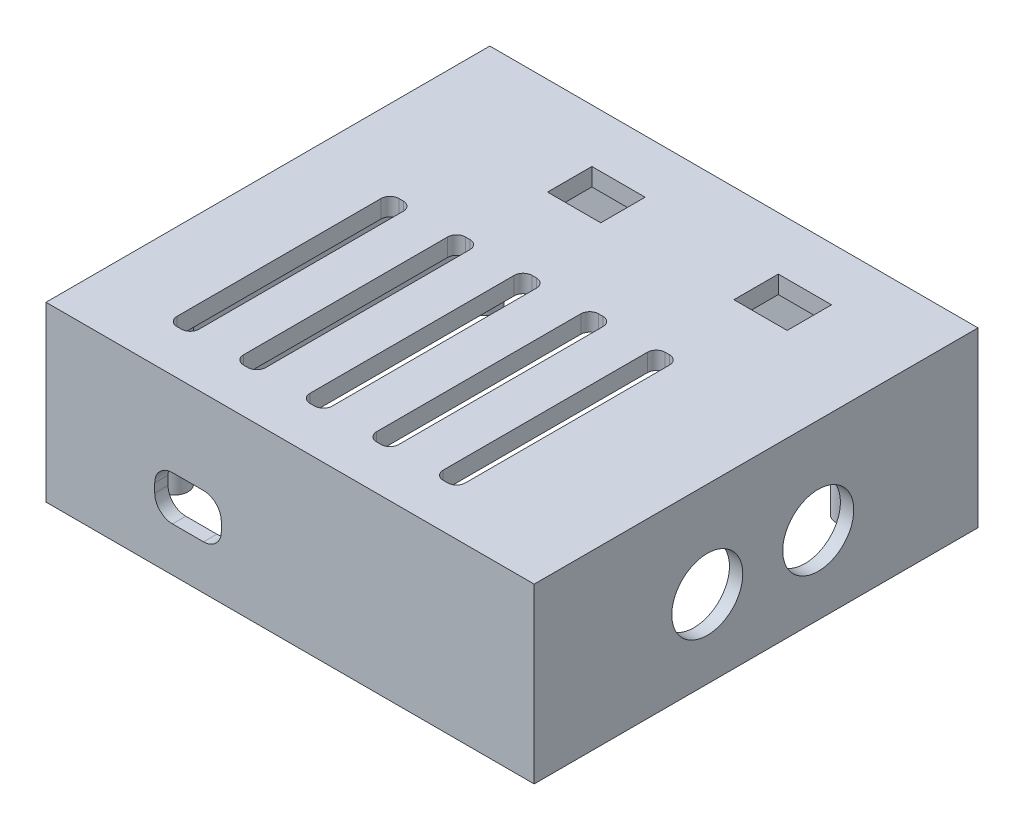
SolidWorks part; units mm, degrees
ref_plane "Front Plane" through (0, 0, 0) normal (0, 0, 1) x (1, 0, 0)
ref_plane "Top Plane" through (0, 0, 0) normal (0, 1, 0) x (1, 0, 0)
ref_plane "Right Plane" through (0, 0, 0) normal (1, 0, 0) x (0, 0, -1)
sketch "Sketch1" plane through (0, 0, 0) normal (0, 1, 0) x (1, 0, 0)
  line L1 (-55, 50) -> (55, 50)
  line L2 (-55, 50) -> (-55, -50)
  line L3 (-55, -50) -> (55, -50)
  line L4 (55, 50) -> (55, -50)
  line L5 (-55, 50) -> (55, -50) construction
  line L6 (-55, -50) -> (55, 50) construction
  point P0 (0, 0)
  dimension "D1" = 110
  dimension "D2" = 100
extrude "Boss-Extrude1" add sketch "Sketch1" along normal blind 1 and the other way blind 3
sketch "Sketch2" plane through (0, -3, 0) normal (0, -1, 0) x (1, 0, 0)
  line L0 (-55, 50) -> (55, 50)
  line L1 (55, 50) -> (55, -50)
  line L2 (55, -50) -> (-55, -50)
  line L3 (-55, -50) -> (-55, 50)
  line L4 (-52, 47) -> (52, 47)
  line L5 (-52, 47) -> (-52, -47)
  line L6 (52, 47) -> (52, -47)
  line L7 (52, -47) -> (-52, -47)
  dimension "D1" = 3
  dimension "D2" = 104
  dimension "D3" = 3
  dimension "D4" = 94
extrude "Boss-Extrude2" add sketch "Sketch2" along normal blind 35
sketch "Sketch3" plane through (0, -3, 0) normal (0, -1, 0) x (1, 0, 0)
  line L0 (0, 63.0039) -> (0, -70.5817) construction
  line L1 (-86.8199, 0) -> (87.9024, 0) construction
  line L2 (55, 50) -> (-55, 50) construction
  line L3 (-55, 50) -> (-55, -50) construction
  circle A0 centre (-41, 35) radius 3
  circle A1 centre (-41, 35) radius 1.3
  circle A2 centre (-41, -35) radius 3
  circle A3 centre (-41, -35) radius 1.3
  circle A4 centre (41, -35) radius 3
  circle A5 centre (41, -35) radius 1.3
  circle A6 centre (41, 35) radius 3
  circle A7 centre (41, 35) radius 1.3
  dimension "D1" = 6
  dimension "D2" = 15
  dimension "D3" = 14
extrude "Boss-Extrude3" add sketch "Sketch3" along normal blind 32 contours A3 | A2 | A0 | A1 | A5 | A4 | A7 | A6
sketch "Sketch5" plane through (0, 0, -50) normal (0, 0, -1) x (-1, 0, 0)
  line L0 (55, -38) -> (-55, -38) construction
  line L1 (-34, -18) -> (-22, -18)
  line L2 (-34, -18) -> (-34, -38)
  line L3 (-34, -38) -> (-22, -38)
  line L4 (-22, -18) -> (-22, -38)
  line L5 (-34, -18) -> (-22, -38) construction
  line L6 (-34, -38) -> (-22, -18) construction
  line L7 (-55, -38) -> (-55, 1) construction
  line L9 (8, -18) -> (20, -18)
  line L10 (8, -18) -> (8, -38)
  line L11 (8, -38) -> (20, -38)
  line L12 (20, -18) -> (20, -38)
  line L13 (8, -18) -> (20, -38) construction
  line L14 (8, -38) -> (20, -18) construction
  point P0 (-28, -28)
  point P9 (14, -28)
  dimension "D1" = 20
  dimension "D2" = 12
  dimension "D3" = 27
  dimension "D4" = 20
  dimension "D5" = 12
  dimension "D6" = 69
extrude "Cut-Extrude5" cut sketch "Sketch5" against normal blind 32 contours L12 L9 L10 L3
sketch "Sketch6" plane through (0, 0, 50) normal (0, 0, 1) x (1, 0, 0)
  line L0 (-55, -38) -> (-55, 1) construction
  line L1 (-30.5, -18) -> (-15.5, -18)
  line L2 (-30.5, -18) -> (-30.5, -28)
  line L3 (-30.5, -28) -> (-15.5, -28)
  line L4 (-15.5, -18) -> (-15.5, -28)
  line L5 (-30.5, -18) -> (-15.5, -28) construction
  line L6 (-30.5, -28) -> (-15.5, -18) construction
  line L7 (55, -38) -> (-55, -38) construction
  point P0 (-23, -23)
  dimension "D1" = 10
  dimension "D2" = 15
  dimension "D3" = 32
  dimension "D4" = 15
extrude "Cut-Extrude6" cut sketch "Sketch6" against normal blind 32
sketch "Sketch7" plane through (55, 0, 0) normal (1, 0, 0) x (0, 0, -1)
  line L0 (-50, -38) -> (-50, 1) construction
  line L1 (50, -38) -> (-50, -38) construction
  circle A0 centre (-11, -20.5) radius 8
  circle A1 centre (14, -20.5) radius 8
  dimension "D1" = 16
  dimension "D2" = 39
  dimension "D3" = 64
  dimension "D4" = 17.5
extrude "Cut-Extrude7" cut sketch "Sketch7" against normal blind 22
sketch "Sketch8" plane through (0, 1, 0) normal (0, 1, 0) x (1, 0, 0)
  line L0 (55, -50) -> (55, 50) construction
  line L1 (34, 28) -> (22, 28)
  line L2 (34, 28) -> (34, 38)
  line L3 (34, 38) -> (22, 38)
  line L4 (22, 28) -> (22, 38)
  line L5 (34, 28) -> (22, 38) construction
  line L6 (34, 38) -> (22, 28) construction
  line L7 (-8, 38) -> (-20, 38)
  line L8 (-8, 38) -> (-8, 28)
  line L9 (-8, 28) -> (-20, 28)
  line L10 (-20, 38) -> (-20, 28)
  line L11 (-8, 38) -> (-20, 28) construction
  line L12 (-8, 28) -> (-20, 38) construction
  line L13 (55, 50) -> (-55, 50) construction
  point P0 (28, 33)
  point P5 (-14, 33)
  dimension "D1" = 12
  dimension "D2" = 10
  dimension "D3" = 12
  dimension "D4" = 10
  dimension "D5" = 27
  dimension "D6" = 69
  dimension "D7" = 17
  dimension "D8" = 17
extrude "Cut-Extrude8" cut sketch "Sketch8" against normal blind 22
sketch "Sketch9" plane through (0, 1, 0) normal (0, 1, 0) x (1, 0, 0)
  line L0 (-47.1519, -15) -> (47.1194, -15) construction
  line L1 (55, 50) -> (-55, 50) construction
  line L2 (-37.5, -40) -> (-32.5, -40)
  line L3 (-37.5, -40) -> (-37.5, 10)
  line L4 (-37.5, 10) -> (-32.5, 10)
  line L5 (-32.5, -40) -> (-32.5, 10)
  line L6 (-37.5, -40) -> (-32.5, 10) construction
  line L7 (-37.5, 10) -> (-32.5, -40) construction
  line L8 (-22.5, -40) -> (-17.5, -40)
  line L9 (-22.5, -40) -> (-22.5, 10)
  line L10 (-22.5, 10) -> (-17.5, 10)
  line L11 (-17.5, -40) -> (-17.5, 10)
  line L12 (-22.5, -40) -> (-17.5, 10) construction
  line L13 (-22.5, 10) -> (-17.5, -40) construction
  line L14 (-7.5, -40) -> (-2.5, -40)
  line L15 (-7.5, -40) -> (-7.5, 10)
  line L16 (-7.5, 10) -> (-2.5, 10)
  line L17 (-2.5, -40) -> (-2.5, 10)
  line L18 (-7.5, -40) -> (-2.5, 10) construction
  line L19 (-7.5, 10) -> (-2.5, -40) construction
  line L20 (12.5, -40) -> (7.5, -40)
  line L21 (12.5, -40) -> (12.5, 10)
  line L22 (12.5, 10) -> (7.5, 10)
  line L23 (7.5, -40) -> (7.5, 10)
  line L24 (12.5, -40) -> (7.5, 10) construction
  line L25 (12.5, 10) -> (7.5, -40) construction
  line L26 (27.5, -40) -> (22.5, -40)
  line L27 (27.5, -40) -> (27.5, 10)
  line L28 (27.5, 10) -> (22.5, 10)
  line L29 (22.5, -40) -> (22.5, 10)
  line L30 (27.5, -40) -> (22.5, 10) construction
  line L31 (27.5, 10) -> (22.5, -40) construction
  line L32 (-55, 50) -> (-55, -50) construction
  point P3 (-35, -15)
  point P8 (-20, -15)
  point P13 (-5, -15)
  point P18 (10, -15)
  point P23 (25, -15)
  dimension "D1" = 5
  dimension "D2" = 5
  dimension "D3" = 5
  dimension "D4" = 5
  dimension "D5" = 5
  dimension "D6" = 50
  dimension "D7" = 50
  dimension "D8" = 50
  dimension "D9" = 50
  dimension "D10" = 50
  dimension "D11" = 65
  dimension "D12" = 20
  dimension "D13" = 35
  dimension "D14" = 50
  dimension "D15" = 65
  dimension "D16" = 80
extrude "Cut-Extrude9" cut sketch "Sketch9" against normal blind 10
fillet "Fillet1" radius 2 20 edges at (27.5, -1, 40) (12.5, -1, 40) (-2.5, -1, 40) (-17.5, -1, 40) (-32.5, -1, 40) (22.5, -1, 40) (7.5, -1, 40) (-7.5, -1, 40) (-22.5, -1, 40) (-37.5, -1, 40) (-37.5, -1, -10) (-22.5, -1, -10) (-7.5, -1, -10) (7.5, -1, -10) (22.5, -1, -10) (-32.5, -1, -10) (-17.5, -1, -10) (-2.5, -1, -10) (12.5, -1, -10) (27.5, -1, -10)
fillet "Fillet2" radius 3 4 edges at (-8, -18, -48.5) (-20, -18, -48.5) (22, -18, -48.5) (34, -18, -48.5)
fillet "Fillet3" radius 4 4 edges at (-30.5, -28, 48.5) (-30.5, -18, 48.5) (-15.5, -28, 48.5) (-15.5, -18, 48.5)
